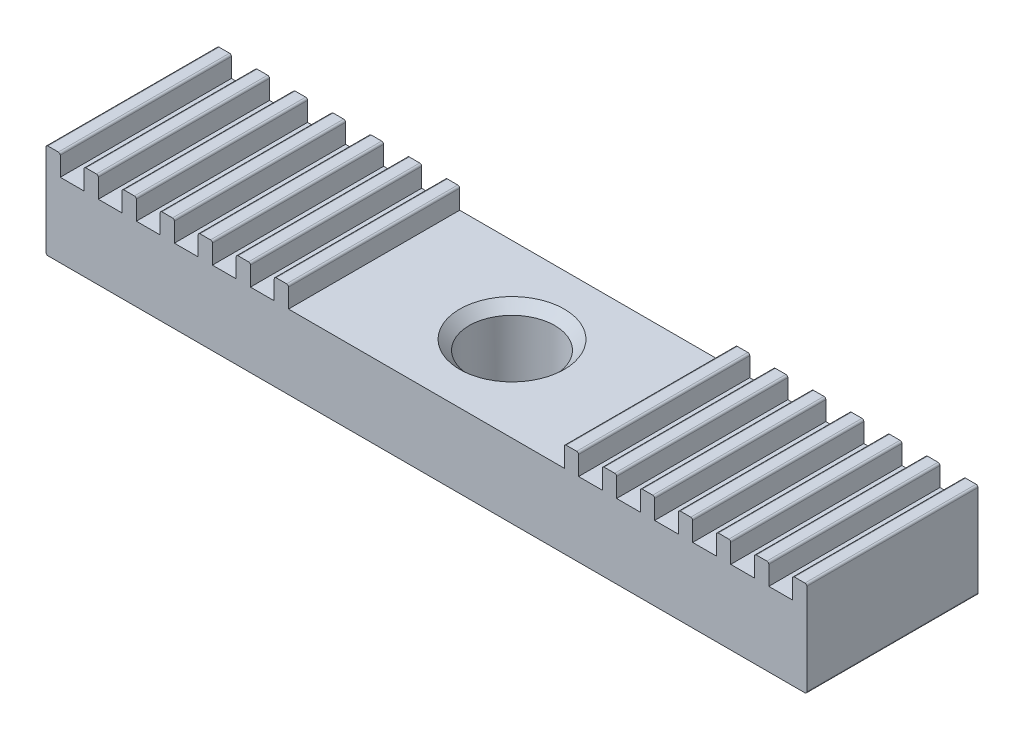
SolidWorks part; units mm, degrees
ref_plane "Front Plane" through (0, 0, 0) normal (0, 0, 1) x (1, 0, 0)
ref_plane "Top Plane" through (0, 0, 0) normal (0, 1, 0) x (1, 0, 0)
ref_plane "Right Plane" through (0, 0, 0) normal (1, 0, 0) x (0, 0, -1)
sketch "Sketch1" plane through (0, 0, 0) normal (0, 0, 1) x (1, 0, 0)
  line L1 (-20, 0) -> (20, 0)
  line L2 (-20, 0) -> (-20, -3.9)
  line L3 (-20, -3.9) -> (20, -3.9)
  line L4 (20, 0) -> (20, -3.9)
  dimension "D1" = 3.9
  dimension "D2" = 40
extrude "Boss-Extrude1" add sketch "Sketch1" along normal blind 9
sketch "Sketch2" plane through (0, 0, 0) normal (0, 1, 0) x (1, 0, 0)
  circle A0 centre (0, -4.5) radius 2.25
  point P2 (0, 0)
  dimension "D1" = 4.5
  dimension "D2" = 4.5
extrude "Cut-Extrude1" cut sketch "Sketch2" against normal up to next
sketch "Sketch3" plane through (0, 0, 9) normal (0, 0, 1) x (1, 0, 0)
  line L0 (-18, 0) -> (-17.25, 0)
  line L1 (-20, 0) -> (-19.25, 0)
  line L2 (-20, 0) -> (-20, 1.1)
  line L3 (-20, 1.1) -> (-19.25, 1.1)
  line L4 (-19.25, 0) -> (-19.25, 1.1)
  line L5 (-18, 0) -> (-18, 1.1)
  line L6 (-18, 1.1) -> (-17.25, 1.1)
  line L7 (-17.25, 0) -> (-17.25, 1.1)
  line L8 (-16, 0) -> (-15.25, 0)
  line L9 (-16, 0) -> (-16, 1.1)
  line L10 (-16, 1.1) -> (-15.25, 1.1)
  line L11 (-15.25, 0) -> (-15.25, 1.1)
  line L12 (-14, 0) -> (-13.25, 0)
  line L13 (-14, 0) -> (-14, 1.1)
  line L14 (-14, 1.1) -> (-13.25, 1.1)
  line L15 (-13.25, 0) -> (-13.25, 1.1)
  line L16 (-12, 0) -> (-11.25, 0)
  line L17 (-12, 0) -> (-12, 1.1)
  line L18 (-12, 1.1) -> (-11.25, 1.1)
  line L19 (-11.25, 0) -> (-11.25, 1.1)
  line L20 (-10, 0) -> (-9.25, 0)
  line L21 (-10, 0) -> (-10, 1.1)
  line L22 (-10, 1.1) -> (-9.25, 1.1)
  line L23 (-9.25, 0) -> (-9.25, 1.1)
  line L24 (-8, 0) -> (-7.25, 0)
  line L25 (-8, 0) -> (-8, 1.1)
  line L26 (-8, 1.1) -> (-7.25, 1.1)
  line L27 (-7.25, 0) -> (-7.25, 1.1)
  line L28 (0, -2.145) -> (0, 2.145) construction
  line L29 (7.25, 0) -> (7.25, 1.1)
  line L30 (8, 1.1) -> (7.25, 1.1)
  line L31 (8, 0) -> (8, 1.1)
  line L32 (8, 0) -> (7.25, 0)
  line L33 (9.25, 0) -> (9.25, 1.1)
  line L34 (10, 1.1) -> (9.25, 1.1)
  line L35 (10, 0) -> (10, 1.1)
  line L36 (10, 0) -> (9.25, 0)
  line L37 (11.25, 0) -> (11.25, 1.1)
  line L38 (12, 1.1) -> (11.25, 1.1)
  line L39 (12, 0) -> (12, 1.1)
  line L40 (12, 0) -> (11.25, 0)
  line L41 (13.25, 0) -> (13.25, 1.1)
  line L42 (14, 1.1) -> (13.25, 1.1)
  line L43 (14, 0) -> (14, 1.1)
  line L44 (14, 0) -> (13.25, 0)
  line L45 (15.25, 0) -> (15.25, 1.1)
  line L46 (16, 1.1) -> (15.25, 1.1)
  line L47 (16, 0) -> (16, 1.1)
  line L48 (16, 0) -> (15.25, 0)
  line L49 (17.25, 0) -> (17.25, 1.1)
  line L50 (18, 1.1) -> (17.25, 1.1)
  line L51 (18, 0) -> (18, 1.1)
  line L52 (19.25, 0) -> (19.25, 1.1)
  line L53 (20, 1.1) -> (19.25, 1.1)
  line L54 (20, 0) -> (20, 1.1)
  line L55 (20, 0) -> (19.25, 0)
  line L56 (18, 0) -> (17.25, 0)
  dimension "D1" = 1.1
  dimension "D2" = 0.75
  dimension "D3" = 7
extrude "Boss-Extrude2" add sketch "Sketch3" against normal up to surface (9 mm away) up to face at (0, -1.95, 0)
fillet "Fillet1" radius 0.1 30 edges at (-20, -3.9, 4.5) (20, -3.9, 4.5) (20, 1.1, 4.5) (19.25, 1.1, 4.5) (18, 1.1, 4.5) (17.25, 1.1, 4.5) (16, 1.1, 4.5) (15.25, 1.1, 4.5) (14, 1.1, 4.5) (13.25, 1.1, 4.5) (12, 1.1, 4.5) (11.25, 1.1, 4.5) (10, 1.1, 4.5) (9.25, 1.1, 4.5) (8, 1.1, 4.5) (7.25, 1.1, 4.5) (-7.25, 1.1, 4.5) (-8, 1.1, 4.5) (-9.25, 1.1, 4.5) (-10, 1.1, 4.5) (-11.25, 1.1, 4.5) (-12, 1.1, 4.5) (-13.25, 1.1, 4.5) (-14, 1.1, 4.5) (-15.25, 1.1, 4.5) (-16, 1.1, 4.5) (-17.25, 1.1, 4.5) (-18, 1.1, 4.5) (-19.25, 1.1, 4.5) (-20, 1.1, 4.5)
chamfer "Chamfer1" distance 0.5 angle 45 1 edges at (0, 0, 6.75)
